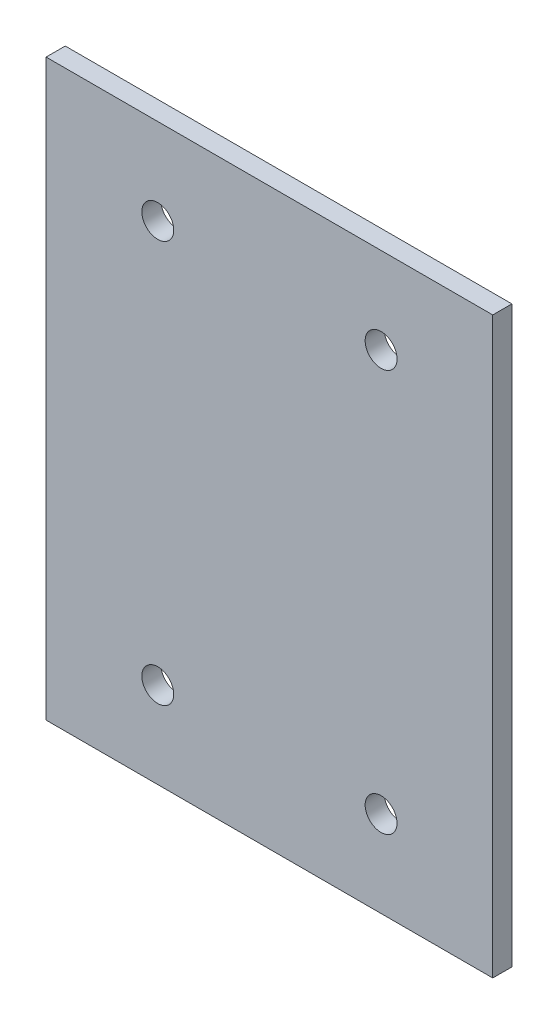
SolidWorks part; units mm, degrees
ref_plane "Plan de face" through (0, 0, 0) normal (0, 0, 1) x (1, 0, 0)
ref_plane "Plan de dessus" through (0, 0, 0) normal (0, 1, 0) x (1, 0, 0)
ref_plane "Plan de droite" through (0, 0, 0) normal (1, 0, 0) x (0, 0, -1)
sketch "Sketch1" plane through (0, 0, 0) normal (0, 0, 1) x (1, 0, 0)
  line L1 (35, -45) -> (-35, -45)
  line L2 (35, -45) -> (35, 45)
  line L3 (35, 45) -> (-35, 45)
  line L4 (-35, -45) -> (-35, 45)
  line L5 (35, -45) -> (-35, 45) construction
  line L6 (35, 45) -> (-35, -45) construction
  point P0 (0, 0)
  dimension "D1" = 70
  dimension "D2" = 90
extrude "Boss-Extrude1" add sketch "Sketch1" along normal blind 3
sketch "Sketch2" plane through (0, 0, 3) normal (0, 0, 1) x (1, 0, 0)
  line L1 (35, 45) -> (-35, 45) construction
  circle A0 centre (-17.5, 31.5) radius 2.5
  circle A1 centre (17.5, 31.5) radius 2.5
  point P4 (0, 0)
  point P6 (17.5, 25.3444)
  point P7 (0, 0)
  point P8 (-17.5, 29.5064)
  point P9 (-17.5, 36.2401)
  dimension "D3" = 5
  dimension "D4" = 5
  dimension "D1" = 35
  dimension "D2" = 17.5
  dimension "D5" = 13.5
extrude "Cut-Extrude1" cut sketch "Sketch2" against normal through all
mirror "Mirror1" about plane through (0, 0, 0) normal (0, 1, 0) of "Cut-Extrude1"
